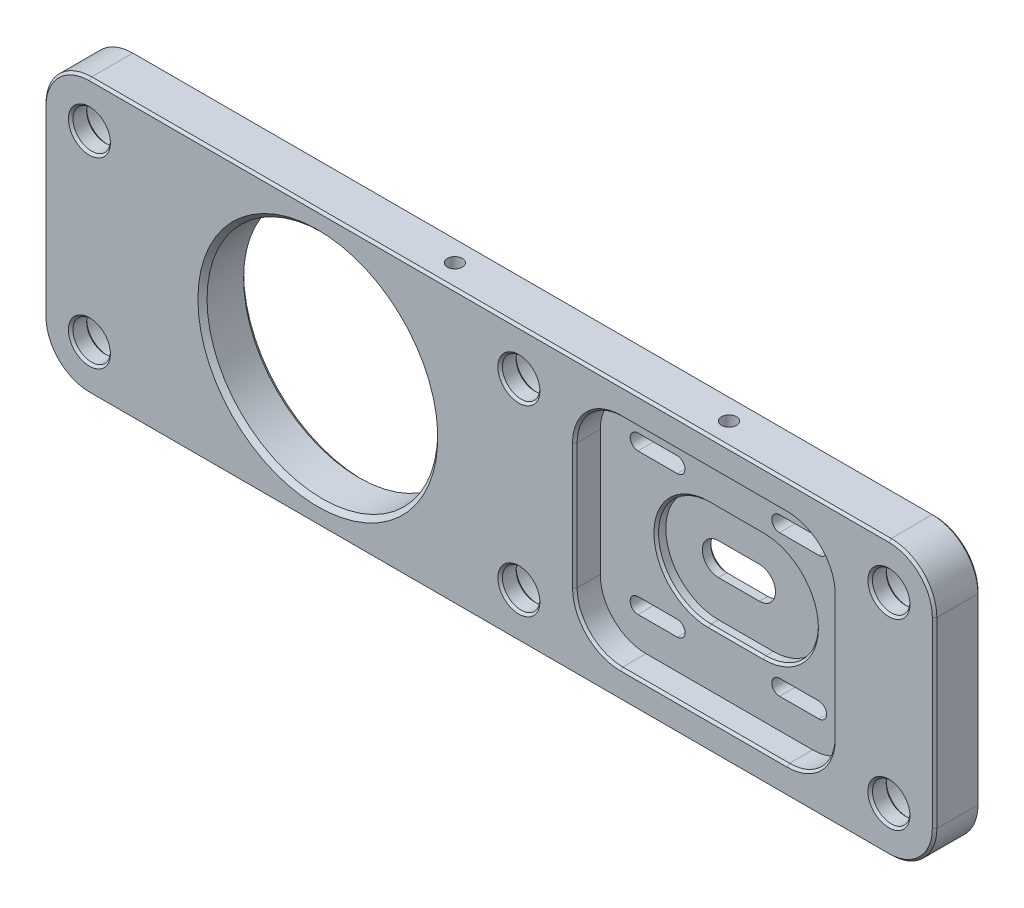
SolidWorks part; units mm, degrees
material "1060 slitina"
ref_plane "Přední rovina" through (0, 0, 0) normal (0, 0, 1) x (1, 0, 0)
ref_plane "Horní rovina" through (0, 0, 0) normal (0, 1, 0) x (1, 0, 0)
ref_plane "Pravá rovina" through (0, 0, 0) normal (1, 0, 0) x (0, 0, -1)
sketch "Skica1" plane through (0, 0, 0) normal (0, 0, 1) x (1, 0, 0)
  line L1 (0, 0) -> (195, 0)
  line L2 (0, 0) -> (0, 60)
  line L3 (0, 60) -> (195, 60)
  line L4 (195, 0) -> (195, 60)
  line L5 (0, 0) -> (195, 60) construction
  line L6 (0, 60) -> (195, 0) construction
  point P4 (97.5, 30)
  dimension "D1" = 60
  dimension "D2" = 195
extrude "Přidat vysunutím1" add sketch "Skica1" along normal blind 10
sketch "Skica2" plane through (0, 0, 10) normal (0, 0, 1) x (1, 0, 0)
  line L0 (0, 30) -> (195, 30) construction
  line L1 (0, 60) -> (0, 0) construction
  line L2 (195, 0) -> (195, 60) construction
  line L3 (133.1, 45.5) -> (124.5, 45.5) construction
  line L4 (124.5, 14.5) -> (155.5, 14.5) construction
  line L5 (124.5, 14.5) -> (124.5, 45.5) construction
  line L6 (124.5, 45.5) -> (155.5, 45.5) construction
  line L7 (155.5, 14.5) -> (155.5, 45.5) construction
  line L8 (124.5, 14.5) -> (155.5, 45.5) construction
  line L9 (124.5, 45.5) -> (155.5, 14.5) construction
  line L10 (133.1, 43.8) -> (124.5, 43.8)
  line L11 (133.1, 47.2) -> (124.5, 47.2)
  line L12 (164.1, 45.5) -> (155.5, 45.5) construction
  line L13 (164.1, 43.8) -> (155.5, 43.8)
  line L14 (164.1, 47.2) -> (155.5, 47.2)
  line L15 (133.1, 14.5) -> (124.5, 14.5) construction
  line L16 (133.1, 16.2) -> (124.5, 16.2)
  line L17 (133.1, 12.8) -> (124.5, 12.8)
  line L18 (164.1, 14.5) -> (155.5, 14.5) construction
  line L19 (164.1, 16.2) -> (155.5, 16.2)
  line L20 (164.1, 12.8) -> (155.5, 12.8)
  line L21 (149, 30) -> (140, 30) construction
  line L22 (149, 26.5) -> (140, 26.5)
  line L23 (149, 33.5) -> (140, 33.5)
  circle A0 centre (140, 30) radius 3.75 construction
  circle A1 centre (124.5, 45.5) radius 1.5 construction
  circle A2 centre (124.5, 14.5) radius 1.5 construction
  circle A3 centre (155.5, 45.5) radius 1.5 construction
  circle A4 centre (155.5, 14.5) radius 1.5 construction
  arc A5 (133.1, 43.8) -> (133.1, 47.2) centre (133.1, 45.5) ccw
  arc A6 (124.5, 47.2) -> (124.5, 43.8) centre (124.5, 45.5) ccw
  arc A7 (164.1, 43.8) -> (164.1, 47.2) centre (164.1, 45.5) ccw
  arc A8 (155.5, 47.2) -> (155.5, 43.8) centre (155.5, 45.5) ccw
  arc A9 (133.1, 16.2) -> (133.1, 12.8) centre (133.1, 14.5) cw
  arc A10 (124.5, 12.8) -> (124.5, 16.2) centre (124.5, 14.5) cw
  arc A11 (164.1, 16.2) -> (164.1, 12.8) centre (164.1, 14.5) cw
  arc A12 (155.5, 12.8) -> (155.5, 16.2) centre (155.5, 14.5) cw
  arc A13 (149, 26.5) -> (149, 33.5) centre (149, 30) ccw
  arc A14 (140, 33.5) -> (140, 26.5) centre (140, 30) ccw
  point P17 (128.8, 45.5)
  point P23 (159.8, 45.5)
  point P29 (128.8, 14.5)
  point P35 (159.8, 14.5)
  point P41 (144.5, 30)
  dimension "D1" = 7.5
  dimension "D4" = 3
  dimension "D5" = 3
  dimension "D6" = 3
  dimension "D7" = 3
  dimension "D10" = 12
  dimension "D12" = 12
  dimension "D14" = 16
  dimension "D2" = 31
  dimension "D3" = 31
  dimension "D8" = 140
  dimension "D9" = 3.4
  dimension "D11" = 3.4
  dimension "D13" = 7
extrude "Odebrat vysunutím1" cut sketch "Skica2" against normal up to surface (10 mm away) up to face at (97.5, 30, 0)
sketch "Skica5" plane through (0, 0, 10) normal (0, 0, 1) x (1, 0, 0)
  line L0 (148, 30) -> (140, 30) construction
  line L1 (148, 19) -> (140, 19)
  line L2 (148, 41) -> (140, 41)
  circle A0 centre (140, 30) radius 3.5 construction
  arc A1 (148, 19) -> (148, 41) centre (148, 30) ccw
  arc A2 (140, 41) -> (140, 19) centre (140, 30) ccw
  point P4 (144, 30)
  dimension "D1" = 22
  dimension "D2" = 8
extrude "Odebrat vysunutím3" cut sketch "Skica5" against normal blind 2
sketch "Skica6" plane through (0, 0, 0) normal (0, 0, -1) x (-1, 0, 0)
  line L0 (-195, 30) -> (0, 30) construction
  line L1 (-195, 0) -> (-195, 60) construction
  line L2 (0, 60) -> (0, 0) construction
  circle A0 centre (-60, 30) radius 25.25
  arc A1 (-140, 26.5) -> (-140, 33.5) centre (-140, 30) ccw construction
  dimension "D1" = 50.5
  dimension "D2" = 80
extrude "Odebrat vysunutím5" cut sketch "Skica6" against normal up to surface (10 mm away) contours A0 up to face at (144, 30, 10)
sketch "Skica8" plane through (0, 0, 10) normal (0, 0, 1) x (1, 0, 0)
  line L0 (0, 30) -> (195, 30) construction
  line L1 (116.25, 53.75) -> (172.75, 53.75)
  line L2 (116.25, 53.75) -> (116.25, 6.25)
  line L3 (116.25, 6.25) -> (172.75, 6.25)
  line L4 (172.75, 53.75) -> (172.75, 6.25)
  line L5 (116.25, 53.75) -> (172.75, 6.25) construction
  line L6 (116.25, 6.25) -> (172.75, 53.75) construction
  line L7 (0, 60) -> (0, 0) construction
  line L8 (195, 0) -> (195, 60) construction
  line L10 (161.25, 8.75) -> (118.75, 8.75) construction
  line L11 (161.25, 8.75) -> (161.25, 51.25) construction
  line L12 (161.25, 51.25) -> (118.75, 51.25) construction
  line L13 (118.75, 8.75) -> (118.75, 51.25) construction
  line L14 (161.25, 8.75) -> (118.75, 51.25) construction
  line L15 (161.25, 51.25) -> (118.75, 8.75) construction
  line L16 (127.75, 8.0874) -> (170.25, 8.0874) construction
  line L17 (127.75, 8.0874) -> (127.75, 51.9126) construction
  line L18 (127.75, 51.9126) -> (170.25, 51.9126) construction
  line L19 (170.25, 8.0874) -> (170.25, 51.9126) construction
  line L20 (127.75, 8.0874) -> (170.25, 51.9126) construction
  line L21 (127.75, 51.9126) -> (170.25, 8.0874) construction
  point P4 (144.5, 30)
  point P5 (149, 30)
  point P13 (140, 30)
  dimension "D1" = 2.5
  dimension "D2" = 42.5
  dimension "D3" = 42.5
  dimension "D4" = 2.5
  dimension "D5" = 2.5
  dimension "D6" = 42.5
extrude "Odebrat vysunutím7" cut sketch "Skica8" against normal blind 5.57
sketch "Skica9" plane through (0, 0, 4.43) normal (0, 0, 1) x (1, 0, 0)
  line L0 (152, 30) -> (140, 30) construction
  line L1 (152, 18.5) -> (140, 18.5)
  line L2 (152, 41.5) -> (140, 41.5)
  arc A0 (152, 18.5) -> (152, 41.5) centre (152, 30) ccw
  arc A1 (140, 41.5) -> (140, 18.5) centre (140, 30) ccw
  point P2 (146, 30)
  dimension "D2" = 35
  dimension "D1" = 23
extrude "Odebrat vysunutím8" cut sketch "Skica9" against normal blind 2.1
chamfer "Zkosení2" distance 1 angle 45 2 edges at (34.75, 30, 0) (34.75, 30, 10)
sketch "Skica11" plane through (0, 0, 0) normal (0, 0, -1) x (-1, 0, 0)
  line L0 (0, 30) -> (-195, 30) construction
  line L1 (0, 60) -> (0, 0) construction
  line L2 (-195, 0) -> (-195, 60) construction
  circle A0 centre (-95, 30) radius 1.5
  dimension "D1" = 3
  dimension "D2" = 95
extrude "Odebrat vysunutím9" [suppressed] cut sketch "Skica11" against normal up to surface (10 mm away)
chamfer "Zkosení3" [suppressed] distance 0.5 angle 45
cosmetic thread "Kosmetický závit1" [suppressed] parameters "D2"=4
chamfer "Zkosení4" distance 0.5 angle 45 4 edges at (136.5, 30, 0) (144.5, 26.5, 0) (144.5, 33.5, 0) (152.5, 30, 0)
fillet "Zaoblit2" radius 10 4 edges at (195, 0, 5) (195, 60, 5) (0, 0, 5) (0, 60, 5)
sketch "Skica12" plane through (0, 0, 0) normal (0, 0, -1) x (-1, 0, 0)
  line L1 (-10, 50) -> (-290, 50) construction
  line L2 (-10, 50) -> (-10, 10) construction
  line L3 (-10, 10) -> (-290, 10) construction
  line L4 (-290, 50) -> (-290, 10) construction
  line L5 (-10, 50) -> (-290, 10) construction
  line L6 (-10, 10) -> (-290, 50) construction
  circle A0 centre (-10, 50) radius 4.1
  circle A1 centre (-10, 10) radius 4.1
  circle A4 centre (-104, 50) radius 4.1
  circle A5 centre (-104, 10) radius 4.1
  circle A6 centre (-185, 50) radius 4.1
  circle A7 centre (-185, 10) radius 4.1
  arc A9 (0, 50) -> (-10, 60) centre (-10, 50) ccw construction
  point P6 (-150, 30)
  dimension "D1" = 8.2
  dimension "D6" = 8.2
  dimension "D7" = 94
  dimension "D8" = 8.2
  dimension "D9" = 8.2
  dimension "D10" = 8.2
  dimension "D12" = 8.2
  dimension "D2" = 175
  dimension "D3" = 40
  dimension "D11" = 81
extrude "Odebrat vysunutím10" cut sketch "Skica12" against normal up to surface (10 mm away) up to face at (33.75, 30, 10)
sketch "Skica13" plane through (0, 0, 0) normal (0, 0, -1) x (-1, 0, 0)
  circle A0 centre (-10, 50) radius 7.5
  circle A1 centre (-10, 10) radius 7.5
  circle A2 centre (-104, 50) radius 7.5
  circle A3 centre (-104, 10) radius 7.5
  circle A4 centre (-185, 50) radius 7.5
  circle A5 centre (-185, 10) radius 7.5
  dimension "D3" = 15
  dimension "D4" = 15
  dimension "D5" = 15
  dimension "D6" = 15
  dimension "D7" = 15
  dimension "D8" = 15
extrude "Odebrat vysunutím11" cut sketch "Skica13" against normal blind 6
chamfer "Zkosení6" distance 0.5 angle 45 18 edges at (5.9, 10, 10) (5.9, 50, 10) (99.9, 10, 10) (99.9, 50, 10) (180.9, 10, 10) (180.9, 50, 10) (180.9, 50, 6) (180.9, 10, 6) (99.9, 10, 6) (99.9, 50, 6) (5.9, 10, 6) (5.9, 50, 6) (2.5, 50, 0) (2.5, 10, 0) (177.5, 50, 0) (177.5, 10, 0) (96.5, 50, 0) (96.5, 10, 0)
fillet "Zaoblit4" radius 10 4 edges at (116.25, 6.25, 7.215) (172.75, 6.25, 7.215) (172.75, 53.75, 7.215) (116.25, 53.75, 7.215)
chamfer "Zkosení7" distance 0.5 angle 45 16 edges at (97.5, 0, 10) (192.0711, 2.9289, 10) (2.9289, 2.9289, 10) (195, 30, 10) (0, 30, 10) (192.0711, 57.0711, 10) (2.9289, 57.0711, 10) (97.5, 60, 10) (97.5, 0, 0) (192.0711, 2.9289, 0) (2.9289, 2.9289, 0) (195, 30, 0) (0, 30, 0) (192.0711, 57.0711, 0) (2.9289, 57.0711, 0) (97.5, 60, 0)
chamfer "Zkosení8" distance 0.5 angle 45 12 edges at (163.5, 30, 4.43) (146, 41.5, 4.43) (146, 18.5, 4.43) (128.5, 30, 4.43) (172.75, 30, 10) (169.8211, 50.8211, 10) (169.8211, 9.1789, 10) (144.5, 53.75, 10) (144.5, 6.25, 10) (119.1789, 50.8211, 10) (119.1789, 9.1789, 10) (116.25, 30, 10)
sketch "Skica14" plane through (0, 60, 0) normal (0, 1, 0) x (1, 0, 0)
  line L4 (0, -9.5) -> (0, -0.5) construction
  line L5 (185, -10) -> (10, -10) construction
  circle A0 centre (85, -5) radius 1.65
  circle A1 centre (145, -5) radius 1.65
  point P6 (85, -5)
  point P8 (145, -5)
  point P17 (85, -5)
  dimension "D1" = 60
  dimension "D2" = 3.3
  dimension "D3" = 3.3
  dimension "D6" = 5
  dimension "D4" = 85
  dimension "D5" = 5
hole_wizard "M4 závit2" positions "Skica14" profile "Skica22" tap size "M4" standard "ISO"
sketch "Skica22" plane through (85, 60, 5) normal (1, 0, 0) x (0, 0, 1)
  line L0 (0, 0) -> (0, 10.9914)
  line L1 (0, 10.9914) -> (1.65, 10)
  line L2 (1.65, 10) -> (1.65, 0)
  line L5 (1.65, 0) -> (0, 0)
  line L10 (0, 10.9914) -> (-1.65, 10) construction
  line L11 (0, -6.35) -> (0, 107.95) construction
  dimension "Průměr závitníku" = 3.3
  dimension "Hloubka závitníku" = 10
  dimension "Úhel vrtání" = 118
cosmetic thread "Závit díry5" parameters "D1"=8, "D2"=4
cosmetic thread "Závit díry6" parameters "D1"=8, "D2"=4
